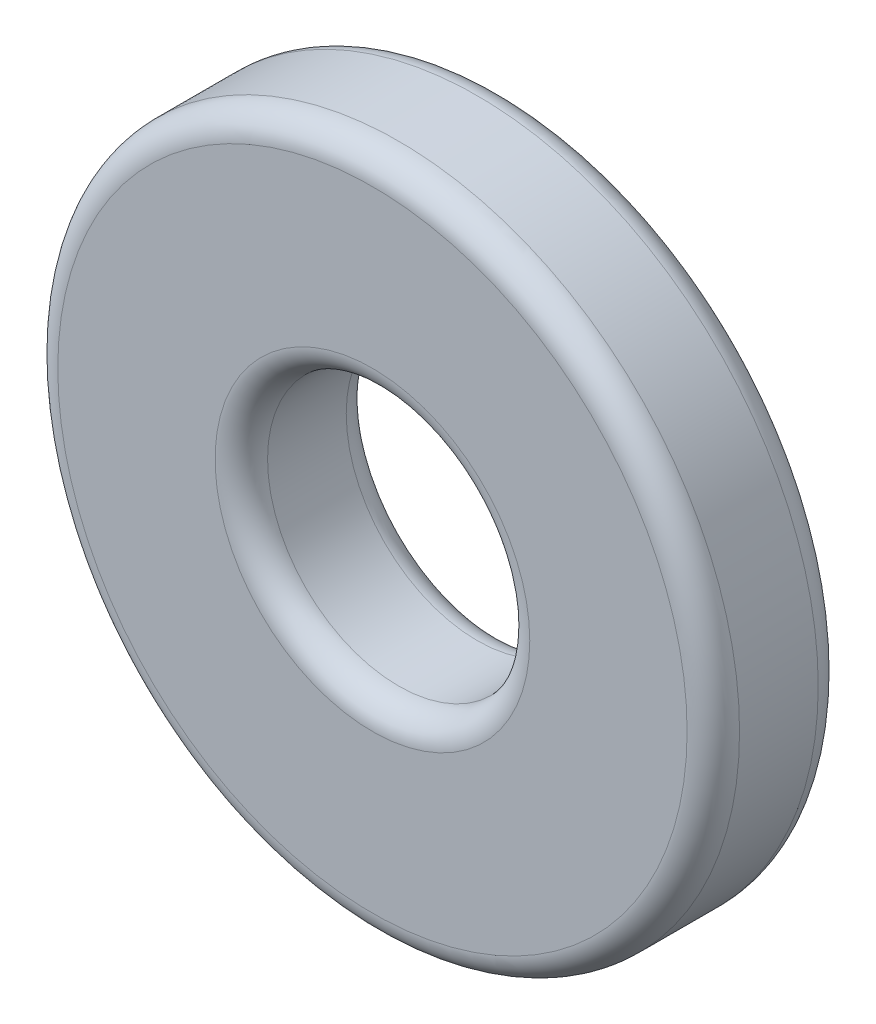
SolidWorks part; units mm, degrees
ref_plane "前视基准面" through (0, 0, 0) normal (0, 0, 1) x (1, 0, 0)
ref_plane "上视基准面" through (0, 0, 0) normal (0, 1, 0) x (1, 0, 0)
ref_plane "右视基准面" through (0, 0, 0) normal (1, 0, 0) x (0, 0, -1)
other "Configuration Table"
sketch "草图1" plane through (0, 0, 0) normal (0, 0, 1) x (1, 0, 0)
  circle A0 centre (0, 0) radius 13
  dimension "diameter" = 26
extrude "Sleeve" add sketch "草图1" along normal blind 5
sketch "草图2" plane through (0, 0, 5) normal (0, 0, 1) x (1, 0, 0)
  circle A0 centre (0, 0) radius 5
  dimension "diameter" = 10
extrude "Bore" cut sketch "草图2" against normal through all
fillet "Rounded_edges" radius 1 4 edges at (5, 0, 5) (5, 0, 0) (13, 0, 0) (13, 0, 5)
